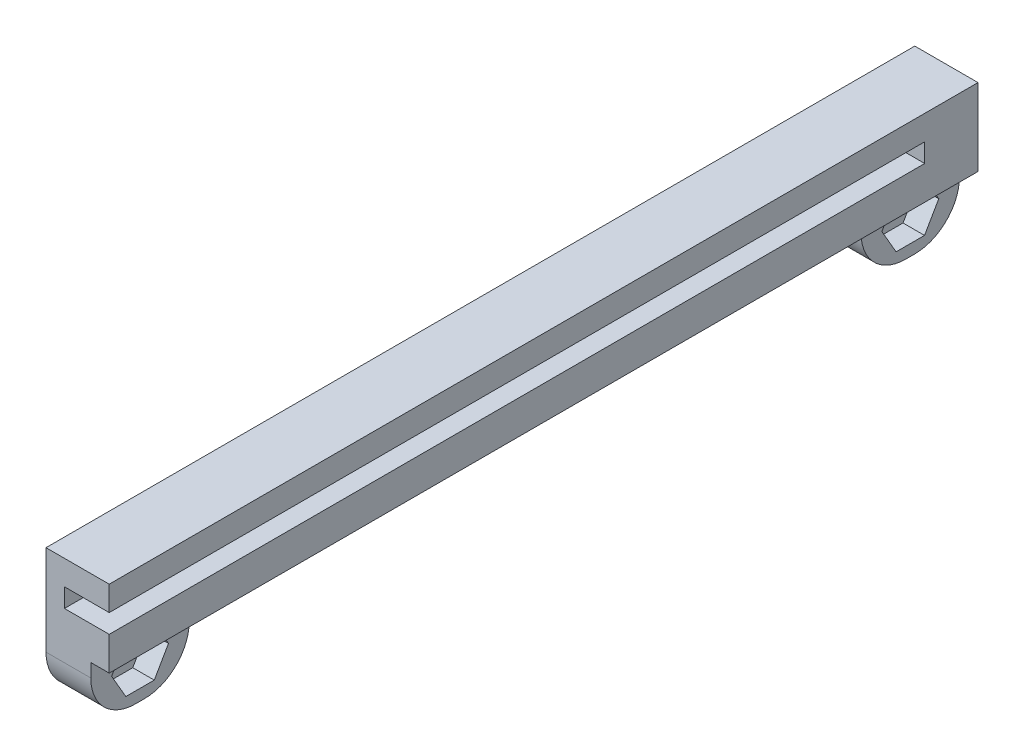
SolidWorks part; units mm, degrees
material "ABS"
ref_plane "Front Plane" through (0, 0, 0) normal (0, 0, 1) x (1, 0, 0)
ref_plane "Top Plane" through (0, 0, 0) normal (0, 1, 0) x (1, 0, 0)
ref_plane "Right Plane" through (0, 0, 0) normal (1, 0, 0) x (0, 0, -1)
sketch "Sketch1" plane through (0, 0, 0) normal (0, 1, 0) x (1, 0, 0)
  line L1 (-3.5288, -48.5) -> (3.5288, -48.5)
  line L2 (-3.5288, -48.5) -> (-3.5288, 48.5)
  line L3 (-3.5288, 48.5) -> (3.5288, 48.5)
  line L4 (3.5288, -48.5) -> (3.5288, 48.5)
  line L5 (-3.5288, -48.5) -> (3.5288, 48.5) construction
  line L6 (-3.5288, 48.5) -> (3.5288, -48.5) construction
  point P0 (0, 0)
  dimension "D1" = 97
  dimension "D2" = 7.0575
extrude "Boss-Extrude2" add sketch "Sketch1" along normal blind 7.6
sketch "Sketch4" plane through (0, 7.6, 0) normal (0, 1, 0) x (1, 0, 0)
  line L0 (3.5288, -48.5) -> (3.5288, 48.5) construction
  line L1 (3.5288, 42.55) -> (-1.4713, 42.55)
  line L2 (3.5288, 42.55) -> (3.5288, -48.5)
  line L3 (3.5288, -48.5) -> (-1.4713, -48.5)
  line L4 (-1.4713, 42.55) -> (-1.4713, -48.5)
  line L5 (-3.5288, -48.5) -> (3.5288, -48.5) construction
  line L7 (-3.5288, 48.5) -> (-3.5288, -48.5) construction
  dimension "D1" = 91.05
  dimension "D2" = 2.0575
extrude "Cut-Extrude1" cut sketch "Sketch4" against normal blind 4.85
sketch "Sketch6" plane through (0, 7.6, 0) normal (0, 1, 0) x (1, 0, 0)
  line L1 (3.5288, 42.55) -> (-1.4713, 42.55)
  line L2 (3.5288, 42.55) -> (3.5288, -48.5)
  line L3 (3.5288, -48.5) -> (-1.4713, -48.5)
  line L4 (-1.4713, 42.55) -> (-1.4713, -48.5)
extrude "Boss-Extrude3" add sketch "Sketch6" against normal blind 2.75
sketch "Sketch8" plane through (0, 0, 0) normal (0, -1, 0) x (1, 0, 0)
  line L1 (-3.5288, 48.5) -> (3.5287, 48.5)
  line L2 (-3.5288, 48.5) -> (-3.5287, -48.5)
  line L3 (-3.5287, -48.5) -> (3.5288, -48.5)
  line L4 (3.5287, 48.5) -> (3.5288, -48.5)
extrude "Boss-Extrude4" add sketch "Sketch8" along normal blind 1
sketch "Sketch9" plane through (0, -1, 0) normal (0, -1, 0) x (1, 0, 0)
  line L1 (-3.5288, 48.5) -> (1.4712, 48.5)
  line L2 (-3.5288, 48.5) -> (-3.5288, 37.5)
  line L3 (-3.5288, 37.5) -> (1.4712, 37.5)
  line L4 (1.4712, 48.5) -> (1.4712, 37.5)
  line L5 (-3.5287, -48.5) -> (1.4713, -48.5)
  line L6 (-3.5287, -48.5) -> (-3.5287, -37.5)
  line L7 (-3.5287, -37.5) -> (1.4713, -37.5)
  line L8 (1.4713, -48.5) -> (1.4713, -37.5)
  point P10 (1.4713, -43)
  dimension "D1" = 11
  dimension "D2" = 11
  dimension "D3" = 5
  dimension "D4" = 5
extrude "Boss-Extrude5" add sketch "Sketch9" along normal blind 6.5 contours L2 L1 L4 L3 | L6 L5 L8 L7
sketch "Sketch10" plane through (1.4713, 0, 0) normal (1, 0, 0) x (0, 0, -1)
  line L0 (-48.5, -7.5) -> (-48.5, -1) construction
  line L1 (-44.5877, -0.75) -> (-46.1754, -3.5)
  line L2 (-46.1754, -3.5) -> (-44.5877, -6.25)
  line L3 (-44.5877, -6.25) -> (-41.4123, -6.25)
  line L4 (-41.4123, -6.25) -> (-39.8246, -3.5)
  line L5 (-39.8246, -3.5) -> (-41.4123, -0.75)
  line L6 (-41.4123, -0.75) -> (-44.5877, -0.75)
  line L7 (-48.5, -7.5) -> (-37.5, -7.5) construction
  line L8 (37.5, -7.5) -> (37.5, -1) construction
  line L9 (46.1754, -3.5) -> (44.5877, -0.75)
  line L10 (44.5877, -0.75) -> (41.4123, -0.75)
  line L11 (41.4123, -0.75) -> (39.8246, -3.5)
  line L12 (39.8246, -3.5) -> (41.4123, -6.25)
  line L13 (41.4123, -6.25) -> (44.5877, -6.25)
  line L14 (44.5877, -6.25) -> (46.1754, -3.5)
  line L15 (48.5, -7.5) -> (37.5, -7.5) construction
  circle A0 centre (-43, -3.5) radius 2.75 construction
  circle A1 centre (43, -3.5) radius 2.75 construction
  dimension "D1" = 5.5
  dimension "D2" = 5.5
  dimension "D3" = 1.25
  dimension "D4" = 5.5
  dimension "D5" = 1.25
  dimension "D6" = 5.5
extrude "Cut-Extrude2" cut sketch "Sketch10" against normal blind 2.4
sketch "Sketch11" plane through (-0.9287, 0, 0) normal (1, 0, 0) x (0, 0, -1)
  line L2 (-48.5, -7.5) -> (-37.5, -7.5) construction
  line L3 (-48.5, -7.5) -> (-48.5, -1) construction
  line L4 (37.5, -7.5) -> (37.5, -1) construction
  line L5 (48.5, -7.5) -> (37.5, -7.5) construction
  circle A0 centre (-43, -3.5) radius 1.85
  circle A1 centre (43, -3.5) radius 1.85
  dimension "D3" = 3.7
  dimension "D4" = 3.7
  dimension "D1" = 4
  dimension "D2" = 5.5
  dimension "D5" = 5.5
  dimension "D6" = 4
extrude "Cut-Extrude3" cut sketch "Sketch11" against normal through all contours A0 | A1
fillet "Fillet2" radius 5 4 edges at (-1.0287, -7.5, -48.5) (-1.0287, -7.5, -37.5) (-1.0288, -7.5, 37.5) (-1.0288, -7.5, 48.5)
mirror "Mirror2" [suppressed]
delete or keep bodies "Body-Delete/Keep 1" [suppressed] type delete bodies bodies 109
